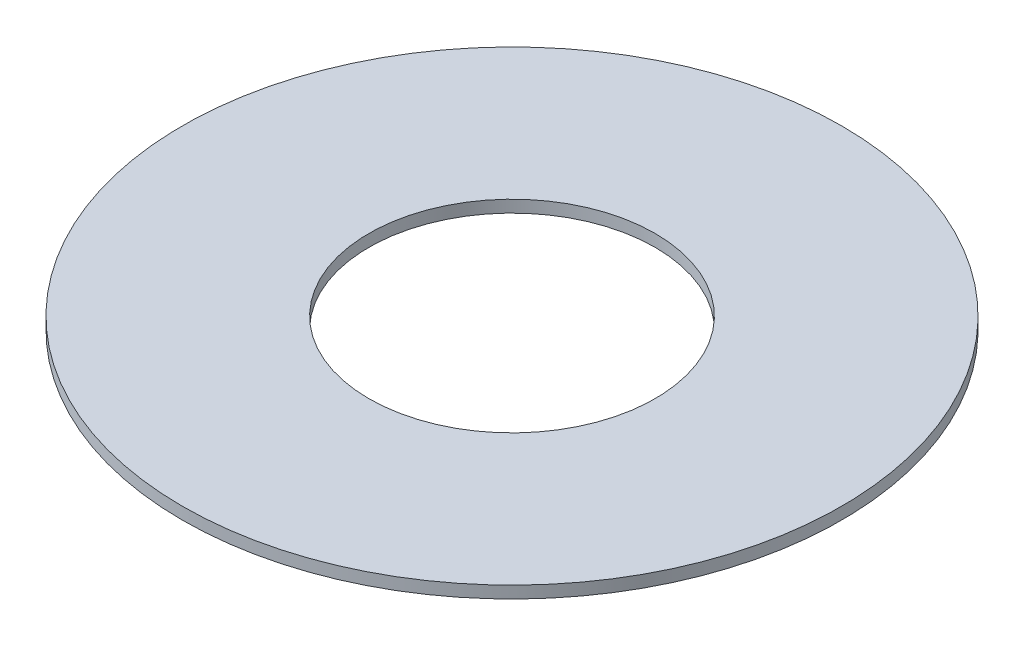
SolidWorks part; units mm, degrees
ref_plane "Front Plane" through (0, 0, 0) normal (0, 0, 1) x (1, 0, 0)
ref_plane "Top Plane" through (0, 0, 0) normal (0, 1, 0) x (1, 0, 0)
ref_plane "Right Plane" through (0, 0, 0) normal (1, 0, 0) x (0, 0, -1)
sketch "Sketch1" plane through (0, 0, 0) normal (0, 1, 0) x (1, 0, 0)
  circle A0 centre (0, 0) radius 9.652
  circle A1 centre (0, 0) radius 22.225
  dimension "D1" = 44.45
  dimension "D2" = 19.304
extrude "Boss-Extrude1" add sketch "Sketch1" along normal blind 0.8128
